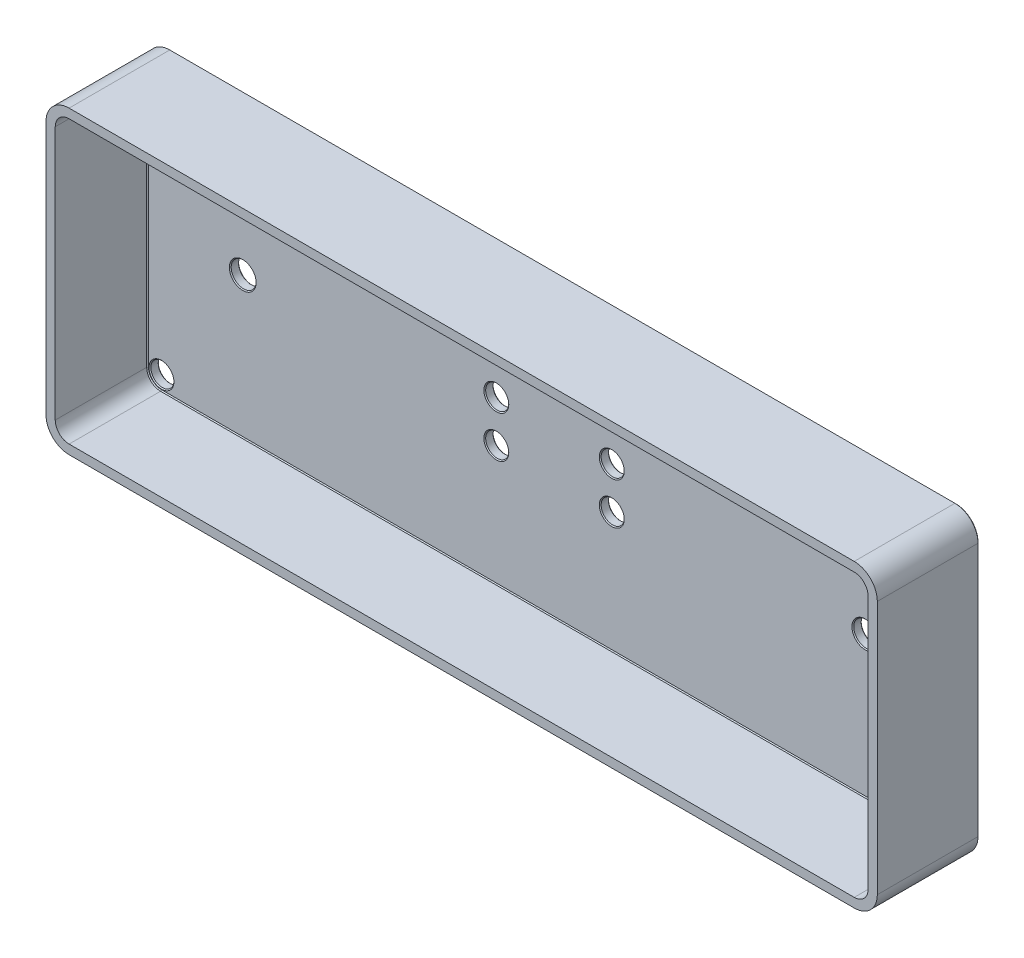
SolidWorks part; units mm, degrees
ref_plane "Front Plane" through (0, 0, 0) normal (0, 0, 1) x (1, 0, 0)
ref_plane "Top Plane" through (0, 0, 0) normal (0, 1, 0) x (1, 0, 0)
ref_plane "Right Plane" through (0, 0, 0) normal (1, 0, 0) x (0, 0, -1)
sketch "Sketch3" plane through (0, 0, 0) normal (0, 0, 1) x (1, 0, 0)
  line L0 (-15.875, 5.7326) -> (15.875, 5.7326) construction
  line L1 (107.95, -41.275) -> (-107.95, -41.275)
  line L2 (114.3, -34.925) -> (114.3, 34.925)
  line L3 (107.95, 41.275) -> (-107.95, 41.275)
  line L4 (-114.3, -34.925) -> (-114.3, 34.925)
  line L5 (114.3, -41.275) -> (-114.3, 41.275) construction
  line L6 (114.3, 41.275) -> (-114.3, -41.275) construction
  line L12 (72.898, 12.7) -> (72.898, -12.7) construction
  line L13 (72.898, -12.7) -> (98.298, -12.7) construction
  line L14 (98.298, -12.7) -> (98.298, 12.7) construction
  line L15 (98.298, 12.7) -> (72.898, 12.7) construction
  line L16 (72.898, 12.7) -> (98.298, -12.7) construction
  line L17 (98.298, 12.7) -> (72.898, -12.7) construction
  line L18 (-98.298, 12.7) -> (-72.898, 12.7) construction
  line L19 (-72.898, 12.7) -> (-72.898, -12.7) construction
  line L20 (-72.898, -12.7) -> (-98.298, -12.7) construction
  line L21 (-98.298, -12.7) -> (-98.298, 12.7) construction
  line L22 (-98.298, 12.7) -> (-72.898, -12.7) construction
  line L23 (-72.898, 12.7) -> (-98.298, -12.7) construction
  line L24 (-15.875, -5.7326) -> (15.875, 5.7326) construction
  line L25 (-15.875, 5.7326) -> (15.875, -5.7326) construction
  line L26 (15.875, 5.7326) -> (15.875, -5.7326) construction
  line L27 (15.875, -5.7326) -> (-15.875, -5.7326) construction
  line L28 (-15.875, -5.7326) -> (-15.875, 5.7326) construction
  line L29 (-15.875, 5.7326) -> (15.875, -5.7326) construction
  line L30 (15.875, 5.7326) -> (-15.875, -5.7326) construction
  arc A0 (114.3, 34.925) -> (107.95, 41.275) centre (107.95, 34.925) ccw
  arc A1 (107.95, -41.275) -> (114.3, -34.925) centre (107.95, -34.925) ccw
  arc A2 (-107.95, -41.275) -> (-114.3, -34.925) centre (-107.95, -34.925) cw
  arc A3 (-107.95, 41.275) -> (-114.3, 34.925) centre (-107.95, 34.925) ccw
  circle A8 centre (-107.95, 34.925) radius 3.175
  circle A9 centre (-107.95, -34.925) radius 3.175
  circle A10 centre (107.95, -34.925) radius 3.175
  circle A11 centre (107.95, 34.925) radius 3.175
  circle A24 centre (-85.598, 0) radius 3.429
  circle A25 centre (85.598, 0) radius 3.429
  circle A26 centre (-15.875, 5.7326) radius 3.175
  circle A27 centre (15.875, 5.7326) radius 3.175
  circle A28 centre (15.875, -5.7326) radius 3.175
  circle A29 centre (-15.875, -5.7326) radius 3.175
  point P0 (0, 0)
  point P22 (-114.3, 0)
  point P23 (0, 0)
  point P57 (-98.298, 0)
  dimension "D3" = 6.35
  dimension "D6" = 16.002
  dimension "D7" = 6.35
  dimension "D8" = 16.002
  dimension "D9" = 28.575
  dimension "D10" = 31.75
  dimension "D11" = 6.35
  dimension "D14" = 25.4
  dimension "D4" = 6.858
  dimension "D5" = 6.858
  dimension "D1" = 82.55
  dimension "D2" = 228.6
  dimension "D12" = 25.4
extrude "Boss-Extrude1" add sketch "Sketch3" along normal blind 27.94
sketch "Sketch4" plane through (0, 0, 27.94) normal (0, 0, 1) x (1, 0, 0)
  line L0 (107.95, 38.735) -> (-107.95, 38.735)
  line L1 (-111.76, 34.925) -> (-111.76, -34.925)
  line L2 (-107.95, -38.735) -> (107.95, -38.735)
  line L3 (111.76, -34.925) -> (111.76, 34.925)
  line L4 (107.95, 41.275) -> (-107.95, 41.275)
  line L5 (-114.3, 34.925) -> (-114.3, -34.925)
  line L6 (-107.95, -41.275) -> (107.95, -41.275)
  line L7 (114.3, -34.925) -> (114.3, 34.925)
  line L8 (107.95, 41.275) -> (-107.95, 41.275)
  line L9 (-114.3, 34.925) -> (-114.3, -34.925)
  line L10 (-107.95, -41.275) -> (107.95, -41.275)
  line L11 (114.3, -34.925) -> (114.3, 34.925)
  arc A0 (111.76, 34.925) -> (107.95, 38.735) centre (107.95, 34.925) ccw
  arc A1 (-107.95, 38.735) -> (-111.76, 34.925) centre (-107.95, 34.925) ccw
  arc A2 (-111.76, -34.925) -> (-107.95, -38.735) centre (-107.95, -34.925) ccw
  arc A3 (107.95, -38.735) -> (111.76, -34.925) centre (107.95, -34.925) ccw
  arc A4 (114.3, 34.925) -> (107.95, 41.275) centre (107.95, 34.925) ccw
  arc A5 (-107.95, 41.275) -> (-114.3, 34.925) centre (-107.95, 34.925) ccw
  arc A6 (-114.3, -34.925) -> (-107.95, -41.275) centre (-107.95, -34.925) ccw
  arc A7 (107.95, -41.275) -> (114.3, -34.925) centre (107.95, -34.925) ccw
  arc A8 (114.3, 34.925) -> (107.95, 41.275) centre (107.95, 34.925) ccw
  arc A9 (-107.95, 41.275) -> (-114.3, 34.925) centre (-107.95, 34.925) ccw
  arc A10 (-114.3, -34.925) -> (-107.95, -41.275) centre (-107.95, -34.925) ccw
  arc A11 (107.95, -41.275) -> (114.3, -34.925) centre (107.95, -34.925) ccw
  dimension "D1" = 0
  dimension "D2" = 2.54
extrude "Cut-Extrude1" cut sketch "Sketch4" against normal blind 25.4 contours A0 L0 A1 L1 A2 L2 A3 L3
chamfer "Chamfer1" distance 0.254 angle 45 18 edges at (111.125, 34.925, 0) (111.125, -34.925, 0) (-104.775, -34.925, 0) (-104.775, 34.925, 0) (89.027, 0, 0) (-82.169, 0, 0) (0, 41.275, 0) (-112.4401, 39.4151, 0) (-114.3, 0, 0) (-112.4401, -39.4151, 0) (0, -41.275, 0) (112.4401, -39.4151, 0) (114.3, 0, 0) (112.4401, 39.4151, 0) (-12.7, -5.7326, 0) (19.05, -5.7326, 0) (19.05, 5.7326, 0) (-12.7, 5.7326, 0)
chamfer "Chamfer2" distance 0.254 angle 45 18 edges at (110.6441, -37.6191, 2.54) (0, -38.735, 2.54) (-110.6441, -37.6191, 2.54) (-111.76, 0, 2.54) (-110.6441, 37.6191, 2.54) (0, 38.735, 2.54) (110.6441, 37.6191, 2.54) (111.76, 0, 2.54) (111.125, 34.925, 2.54) (111.125, -34.925, 2.54) (-104.775, -34.925, 2.54) (-104.775, 34.925, 2.54) (89.027, 0, 2.54) (-82.169, 0, 2.54) (-12.7, -5.7326, 2.54) (19.05, -5.7326, 2.54) (19.05, 5.7326, 2.54) (-12.7, 5.7326, 2.54)
